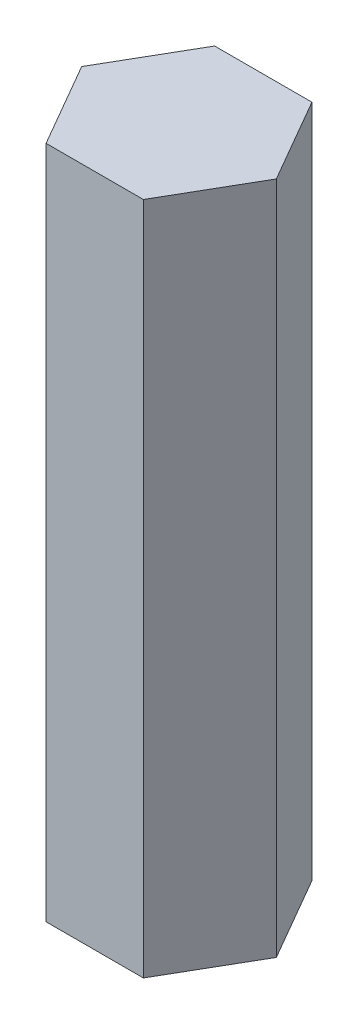
SolidWorks part; units mm, degrees
ref_plane "Front Plane" through (0, 0, 0) normal (0, 0, 1) x (1, 0, 0)
ref_plane "Top Plane" through (0, 0, 0) normal (0, 1, 0) x (1, 0, 0)
ref_plane "Right Plane" through (0, 0, 0) normal (1, 0, 0) x (0, 0, -1)
sketch "Sketch1" plane through (0, 0, 0) normal (0, 1, 0) x (1, 0, 0)
  line L1 (7.3323, 0) -> (3.6662, 6.35)
  line L2 (3.6662, 6.35) -> (-3.6662, 6.35)
  line L3 (-3.6662, 6.35) -> (-7.3323, 0)
  line L4 (-7.3323, 0) -> (-3.6662, -6.35)
  line L5 (-3.6662, -6.35) -> (3.6662, -6.35)
  line L6 (3.6662, -6.35) -> (7.3323, 0)
  circle A0 centre (0, 0) radius 6.35 construction
  dimension "D1" = 12.7
extrude "Boss-Extrude1" add sketch "Sketch1" along normal blind 50.8
